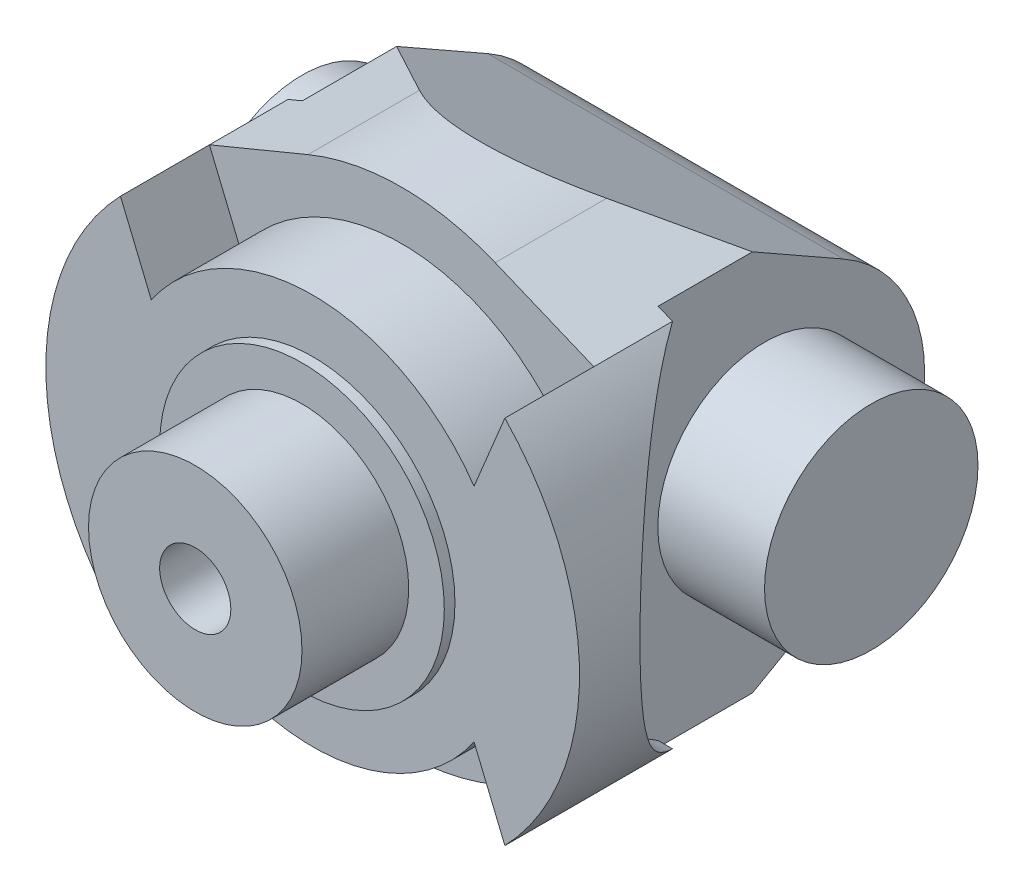
SolidWorks part; units mm, degrees
ref_plane "Front Plane" through (0, 0, 0) normal (0, 0, 1) x (1, 0, 0)
ref_plane "Top Plane" through (0, 0, 0) normal (0, 1, 0) x (1, 0, 0)
ref_plane "Right Plane" through (0, 0, 0) normal (1, 0, 0) x (0, 0, -1)
sketch "Sketch1" plane through (0, 0, 0) normal (0, 0, 1) x (1, 0, 0)
  circle A0 centre (0, 0) radius 6
  dimension "D1" = 12
extrude "Boss-Extrude1" add sketch "Sketch1" along normal blind 11
sketch "Sketch2" plane through (0, 0, 0) normal (1, 0, 0) x (0, 0, -1)
  line L0 (0, -6) -> (0, 6) construction
  line L1 (0, -6) -> (0, 6) construction
  circle A0 centre (0, 0) radius 6
extrude "Boss-Extrude2" add sketch "Sketch2" along normal mid plane 16
sketch "Sketch3" plane through (-8, 0, 0) normal (-1, 0, 0) x (0, 0, 1)
  circle A0 centre (0, 0) radius 3
  circle A1 centre (0, 0) radius 6
  circle A2 centre (0, 0) radius 6
  dimension "D2" = 6
  dimension "D1" = 0
extrude "Cut-Extrude1" cut sketch "Sketch3" against normal blind 3 and the other way blind 10
sketch "Sketch5" plane through (0, 0, 11) normal (0, 0, 1) x (1, 0, 0)
  line L1 (0, -8.6609) -> (8.8681, -8.6609)
  line L2 (0, -8.6609) -> (0, 16.4313)
  line L3 (0, 16.4313) -> (8.8681, 16.4313)
  line L4 (8.8681, -8.6609) -> (8.8681, 16.4313)
extrude "Cut-Extrude3" cut sketch "Sketch5" against normal through all
sketch "Sketch4" plane through (0, 0, 11) normal (0, 0, 1) x (1, 0, 0)
  line L0 (0, 3) -> (0, 6)
  line L1 (0, -6) -> (0, 6)
  line L2 (0, -6) -> (0, -3)
  arc A0 (0, 3) -> (0, -3) centre (0, 0) ccw
  arc A1 (0, 6) -> (0, -6) centre (0, 0) ccw
  arc A2 (0, 6) -> (0, -6) centre (0, 0) ccw
  dimension "D2" = 6
  dimension "D1" = 0
extrude "Cut-Extrude2" cut sketch "Sketch4" against normal blind 3.3
mirror "Mirror1" about plane through (0, -8.6609, -6) normal (-1, 0, 0) of bodies 104
sketch "Sketch7" plane through (0, 0, 7.7) normal (0, 0, 1) x (1, 0, 0)
  line L0 (-4.5357, 3.1108) -> (-5.7325, 6)
  line L1 (-4.5357, 3.1108) -> (-4.5357, -3.1108) construction
  line L2 (-4.5357, 3.1108) -> (4.5357, 3.1108) construction
  line L3 (4.5357, 3.1108) -> (4.5357, -3.1108) construction
  line L4 (-4.5357, -3.1108) -> (4.5357, -3.1108) construction
  line L5 (-4.5357, 3.1108) -> (4.5357, -3.1108) construction
  line L6 (4.5357, 3.1108) -> (-4.5357, -3.1108) construction
  line L7 (-5.7325, 6) -> (-2.9608, 7.1481) construction
  line L8 (-2.9608, 7.1481) -> (0, 0) construction
  line L9 (0, 0) -> (0, 6) construction
  line L10 (4.5357, 3.1108) -> (5.7325, 6)
  line L11 (5.7325, 6) -> (-5.7325, 6)
  line L12 (0, 0) -> (-9.323, 0) construction
  line L13 (4.5357, -3.1108) -> (5.7325, -6)
  line L14 (5.7325, -6) -> (-5.7325, -6)
  line L15 (-4.5357, -3.1108) -> (-5.7325, -6)
  arc A0 (4.5357, 3.1108) -> (-4.5357, 3.1108) centre (0, 0) ccw
  arc A1 (-4.5357, -3.1108) -> (4.5357, -3.1108) centre (0, 0) ccw
  circle A2 centre (0, 0) radius 6 construction
  dimension "D1" = 11
  dimension "D2" = 22.5
  dimension "D3" = 3
extrude "Cut-Extrude5" cut sketch "Sketch7" against normal blind 2.5
sketch "Sketch8" plane through (0, 0, 7.7) normal (0, 0, 1) x (1, 0, 0)
  line L0 (4.7601, 3.6526) -> (5.4022, 5.2026)
  line L1 (-4.7601, 3.6526) -> (-5.4022, 5.2026)
  line L2 (-4.7601, -3.6526) -> (-5.4022, -5.2026)
  line L3 (4.7601, -3.6526) -> (5.4022, -5.2026)
  line L4 (-4.7601, -3.6526) -> (-4.5357, -3.1108)
  line L5 (4.5357, -3.1108) -> (4.7601, -3.6526)
  line L6 (4.7601, 3.6526) -> (4.5357, 3.1108)
  line L7 (-4.5357, 3.1108) -> (-4.7601, 3.6526)
  line L8 (-4.7601, -3.6526) -> (-4.5357, -3.1108) construction
  line L9 (4.5357, -3.1108) -> (4.7601, -3.6526) construction
  line L10 (4.7601, 3.6526) -> (4.5357, 3.1108) construction
  line L11 (-4.5357, 3.1108) -> (-4.7601, 3.6526) construction
  line L13 (-5.4022, 5.2026) -> (-2.6305, 6.3506) construction
  line L14 (-2.9608, 7.1481) -> (0, 0) construction
  arc A0 (-5.4022, 5.2026) -> (-5.4022, -5.2026) centre (0, 0) ccw
  arc A1 (5.4022, -5.2026) -> (5.4022, 5.2026) centre (0, 0) ccw
  circle A2 centre (0, 0) radius 6.8739 construction
  arc A4 (-4.5357, -3.1108) -> (4.5357, -3.1108) centre (0, 0) ccw
  arc A5 (4.7601, -3.6526) -> (4.7601, 3.6526) centre (0, 0) ccw
  arc A6 (4.5357, 3.1108) -> (-4.5357, 3.1108) centre (0, 0) ccw
  arc A7 (-4.7601, 3.6526) -> (-4.7601, -3.6526) centre (0, 0) ccw
  arc A8 (-4.5357, -3.1108) -> (4.5357, -3.1108) centre (0, 0) ccw construction
  arc A9 (4.7601, -3.6526) -> (4.7601, 3.6526) centre (0, 0) ccw
  arc A10 (4.5357, 3.1108) -> (-4.5357, 3.1108) centre (0, 0) ccw construction
  arc A11 (-4.7601, 3.6526) -> (-4.7601, -3.6526) centre (0, 0) ccw
  dimension "D2" = 7.5
  dimension "D1" = 0
extrude "Boss-Extrude3" add sketch "Sketch8" against normal up to surface (2.9399 mm away)
sketch "Sketch9" plane through (0, 0, 5.2) normal (0, 0, 1) x (1, 0, 0)
  line L5 (2.6305, 6.3506) -> (5.4022, 5.2026)
  line L6 (-5.4022, 5.2026) -> (-2.6305, 6.3506)
  line L7 (4.5357, 3.1108) -> (4.7601, 3.6526)
  line L8 (-4.7601, 3.6526) -> (-4.5357, 3.1108)
  line L11 (5.4022, 5.2026) -> (4.7601, 3.6526)
  line L12 (-4.7601, 3.6526) -> (-5.4022, 5.2026)
  arc A6 (2.6305, 6.3506) -> (-2.6305, 6.3506) centre (0, 0) ccw
  arc A9 (4.7601, 3.6526) -> (-4.7601, 3.6526) centre (0, 0) ccw
  arc A10 (4.5357, 3.1108) -> (-4.5357, 3.1108) centre (0, 0) ccw
  arc A11 (4.7601, 3.6526) -> (-4.7601, 3.6526) centre (0, 0) ccw
  dimension "D1" = 0
extrude "Boss-Extrude4" add sketch "Sketch9" against normal up to vertex (11.201 mm away)
sketch "Sketch10" plane through (-5, 0, 0) normal (-1, 0, 0) x (0, 0, 1)
  line L2 (4.2536, 4.2317) -> (2.9889, 4.2317)
  line L4 (2.9889, 4.2317) -> (2.9889, 5.2026)
  circle A0 centre (0, 0) radius 3 construction
  circle A1 centre (0, 0) radius 3
  arc A2 (2.9889, 5.2026) -> (4.2536, -4.2317) centre (0, 0) ccw
  arc A3 (4.2536, -4.2317) -> (4.2536, 4.2317) centre (0, 0) ccw
  arc A4 (2.9889, 5.2026) -> (4.2536, -4.2317) centre (0, 0) ccw
  arc A5 (4.2536, -4.2317) -> (2.9889, 5.2026) centre (0, 0) ccw
  dimension "D1" = 0
extrude "Cut-Extrude6" cut sketch "Sketch10" along normal through all
mirror "Mirror2" about plane through (0, 0, 0) normal (0, 1, 0) of bodies 112 113
sketch "Sketch12" plane through (0, 0, 7.7) normal (0, 0, 1) x (1, 0, 0)
  circle A0 centre (0, 0) radius 3 construction
  circle A1 centre (0, 0) radius 3
  circle A2 centre (0, 0) radius 4
  dimension "D1" = 1
extrude "Boss-Extrude5" add sketch "Sketch12" along normal blind 0.3
sketch "Sketch13" plane through (0, 0, 0) normal (1, 0, 0) x (0, 0, -1)
  line L0 (-2.9889, -6.8739) -> (-2.9889, -6.3506) construction
  line L1 (-2.9889, 6.3506) -> (-2.9889, 6.8739) construction
  line L2 (-2.9889, -6.8739) -> (-2.9889, -5.2026)
  line L3 (-2.9889, 5.2026) -> (-2.9889, 6.8739)
  line L4 (1.3828, 5.8385) -> (-2.9889, 6.8739)
  line L5 (-2.9889, -6.8739) -> (1.3828, -5.8385)
  arc A0 (-2.9889, -5.2026) -> (-2.9889, 5.2026) centre (0, 0) ccw construction
  arc A1 (-2.9889, -5.2026) -> (1.3828, -5.8385) centre (0, 0) ccw
  arc A2 (1.3828, 5.8385) -> (-2.9889, 5.2026) centre (0, 0) ccw
extrude "Boss-Extrude6" add sketch "Sketch13" along normal up to surface and the other way up to surface
sketch "Sketch17" plane through (-5, 0, 0) normal (-1, 0, 0) x (0, 0, 1)
  line L0 (2.9889, -6.8739) -> (-2.223, -3.9126)
  line L1 (2.9889, 6.8739) -> (-2.223, 3.9126)
  line L2 (-2.223, 3.9126) -> (-2.223, -3.9126) construction
  line L3 (-1.3828, 5.8385) -> (2.9889, 6.8739) construction
  line L4 (2.9889, -6.8739) -> (-1.3828, -5.8385) construction
  line L5 (-1.3828, 5.8385) -> (2.9889, 6.8739)
  line L6 (2.9889, -6.8739) -> (-1.3828, -5.8385)
  arc A0 (-2.223, 3.9126) -> (-2.223, -3.9126) centre (0, 0) ccw
  arc A1 (-1.3828, 5.8385) -> (-1.3828, -5.8385) centre (0, 0) ccw construction
  arc A2 (-1.3828, 5.8385) -> (-1.3828, -5.8385) centre (0, 0) ccw
  dimension "D1" = 4.5
extrude "Cut-Extrude12" cut sketch "Sketch17" against normal through all
sketch "Sketch14" plane through (0, 0, 2.9889) normal (0, 0, -1) x (-1, 0, 0)
  line L0 (5, -16.8739) -> (-5, -16.8739)
  line L1 (0, -6.8739) -> (0, -16.8739) construction
  line L3 (-5, -6.8739) -> (0, -6.8739)
  line L4 (-5, -5.3691) -> (-5, -6.8739)
  line L5 (-2.6305, -6.3506) -> (-5, -5.3691)
  line L10 (-5, -5.3691) -> (-5, -16.8739)
  line L13 (-2.6305, -6.3506) -> (-5, -5.3691)
  line L25 (5, -5.3691) -> (2.6305, -6.3506)
  line L26 (5, -6.8739) -> (5, -5.3691)
  line L27 (0, -6.8739) -> (5, -6.8739)
  line L30 (5, -5.3691) -> (2.6305, -6.3506)
  line L31 (5, -16.8739) -> (5, -5.3691)
  arc A1 (-2.6305, -6.3506) -> (0, -6.8739) centre (0, 0) ccw
  arc A2 (-2.6305, -6.3506) -> (0, -6.8739) centre (0, 0) ccw
  arc A3 (0, -6.8739) -> (2.6305, -6.3506) centre (0, 0) ccw
  arc A6 (0, -6.8739) -> (2.6305, -6.3506) centre (0, 0) ccw
  dimension "D1" = 0
  dimension "D2" = 0
extrude "Cut-Extrude9" cut sketch "Sketch14" along normal through all
sketch "Sketch15" plane through (0, 0, 11) normal (0, 0, 1) x (1, 0, 0)
  line L1 (0, 0) -> (-17.302, 0)
  line L2 (0, 0) -> (0, -16.7974)
  line L3 (0, -16.7974) -> (-17.302, -16.7974)
  line L4 (-17.302, 0) -> (-17.302, -16.7974)
extrude "Cut-Extrude10" cut sketch "Sketch15" against normal through all flip side to cut
mirror "Mirror3" about plane through (0, 0, -4.5) normal (0, 1, 0) of bodies 121
mirror "Mirror4" of bodies 122
sketch "Sketch16" plane through (0, 0, 11) normal (0, 0, 1) x (1, 0, 0)
  circle A0 centre (0, 0) radius 1
  dimension "D1" = 2
extrude "Cut-Extrude11" cut sketch "Sketch16" against normal through all
